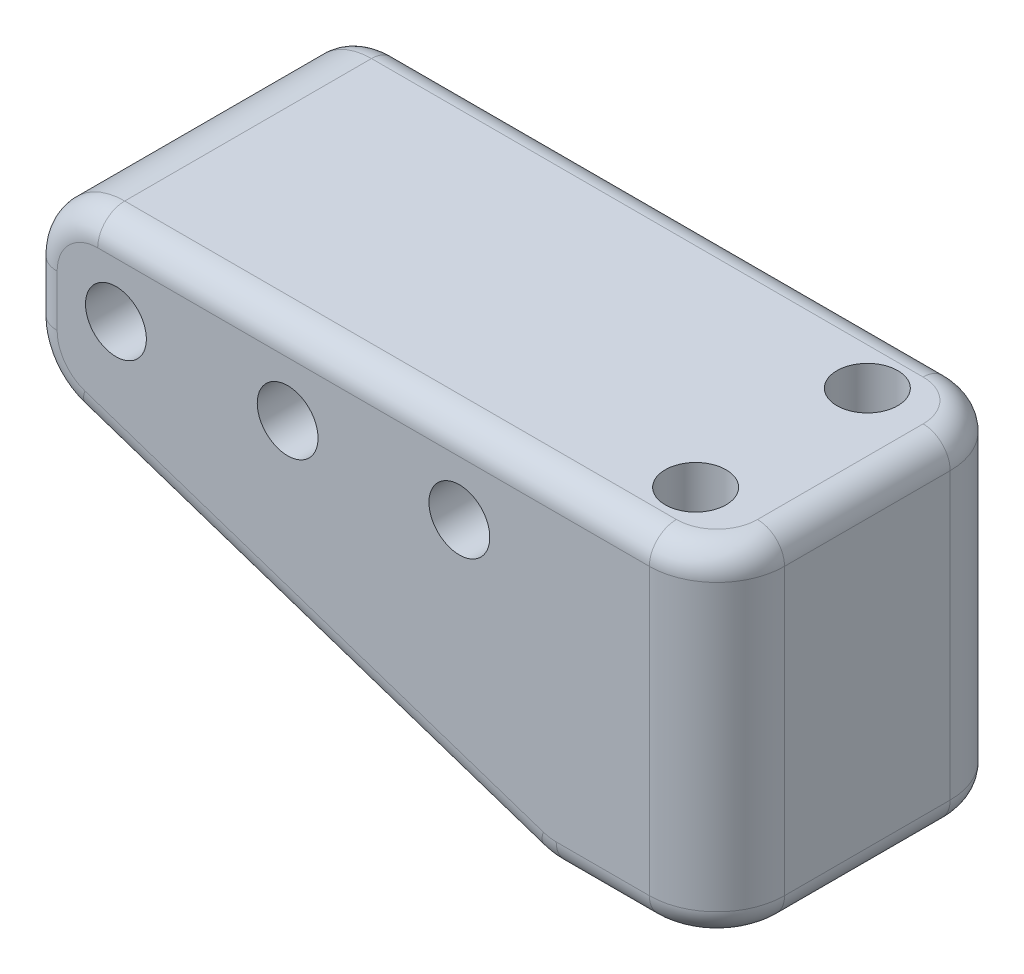
SolidWorks part; units mm, degrees
ref_plane "Front Plane" through (0, 0, 0) normal (0, 0, 1) x (1, 0, 0)
ref_plane "Top Plane" through (0, 0, 0) normal (0, 1, 0) x (1, 0, 0)
ref_plane "Right Plane" through (0, 0, 0) normal (1, 0, 0) x (0, 0, -1)
sketch "Sketch1" plane through (0, 0, 0) normal (0, 0, 1) x (1, 0, 0)
  line L0 (-6.35, -6.35) -> (31.75, -19.05)
  line L1 (-6.35, 6.0452) -> (44.45, 6.0452)
  line L2 (-6.35, 6.0452) -> (-6.35, -6.35)
  line L4 (44.45, 6.0452) -> (44.45, -19.05)
  line L7 (44.45, -19.05) -> (31.75, -19.05)
  circle A0 centre (0, 0) radius 2.25
  circle A1 centre (12.7, 0) radius 2.25
  circle A2 centre (25.4, 0) radius 2.25
  point P13 (0, 0)
  point P14 (0, 0)
  dimension "D1" = 4.5
  dimension "D2" = 6.35
  dimension "D3" = 6.35
  dimension "D4" = 12.7
  dimension "D5" = 50.8
  dimension "D7" = 12.7
  dimension "D8" = 12.3952
  dimension "D6" = 3
extrude "Boss-Extrude1" add sketch "Sketch1" along normal blind 22.2504
sketch "Sketch2" plane through (0, 6.0452, 0) normal (0, 1, 0) x (1, 0, 0)
  line L0 (44.45, -11.1252) -> (-6.35, -11.1252) construction
  line L4 (44.45, 0) -> (-6.35, 0)
  line L5 (-6.35, 0) -> (-6.35, -22.2504)
  line L6 (-6.35, -22.2504) -> (44.45, -22.2504)
  line L7 (44.45, -22.2504) -> (44.45, 0)
  line L8 (44.45, 0) -> (-6.35, 0)
  line L9 (-6.35, 0) -> (-6.35, -22.2504)
  line L10 (-6.35, -22.2504) -> (44.45, -22.2504)
  line L11 (44.45, -22.2504) -> (44.45, 0)
  circle A0 centre (38.1, -4.7752) radius 2.25
  circle A1 centre (38.1, -17.4752) radius 2.25
  dimension "D2" = 4.5
  dimension "D3" = 6.35
  dimension "D4" = 6.35
  dimension "D1" = 0
  dimension "D5" = 2
extrude "Cut-Extrude1" cut sketch "Sketch2" against normal up to next contours A1 | A0
fillet "Fillet1" radius 5 5 edges at (44.45, -6.5024, 0) (44.45, -6.5024, 22.2504) (-6.35, 6.0452, 11.1252) (-6.35, -6.35, 11.1252) (31.75, -19.05, 11.1252)
fillet "Fillet2" radius 2 20 edges at (42.9855, 6.0452, 20.7859) (44.45, 6.0452, 11.1252) (42.9855, 6.0452, 1.4645) (19.05, 6.0452, 0) (-4.8855, 4.5807, 0) (-6.35, -0.8505, 0) (-6.35, -0.8505, 22.2504) (-4.8855, 4.5807, 22.2504) (19.05, 6.0452, 22.2504) (14.0246, -13.1415, 0) (-5.4062, -5.6698, 0) (14.0246, -13.1415, 22.2504) (-5.4062, -5.6698, 22.2504) (31.7605, -18.9854, 0) (36.0057, -19.05, 0) (42.9855, -19.05, 1.4645) (44.45, -19.05, 11.1252) (42.9855, -19.05, 20.7859) (36.0057, -19.05, 22.2504) (31.7605, -18.9854, 22.2504)
